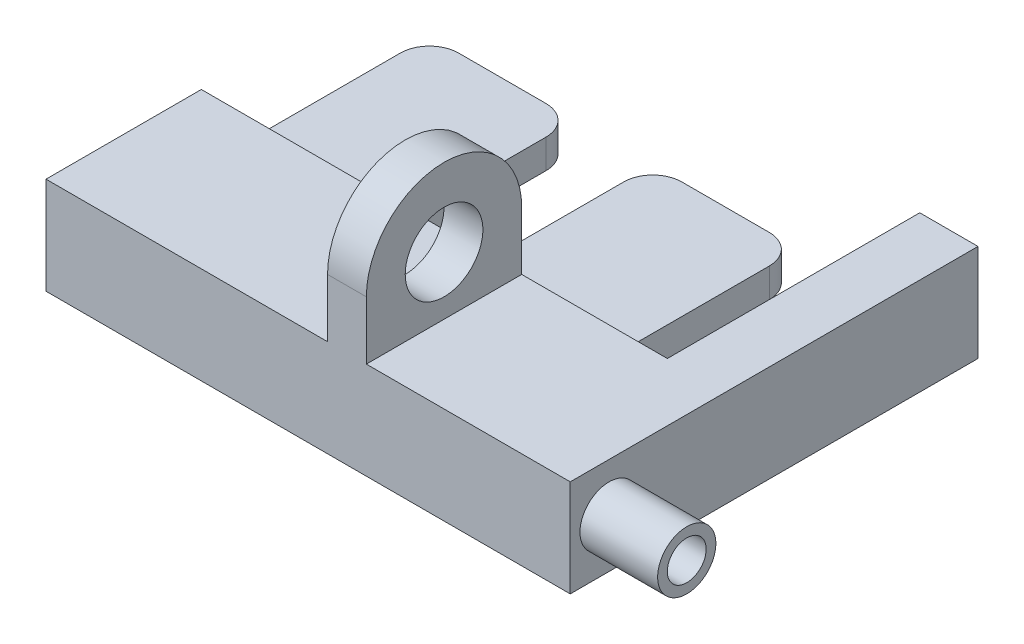
SolidWorks part; units mm, degrees
ref_plane "前视基准面" through (0, 0, 0) normal (0, 0, 1) x (1, 0, 0)
ref_plane "上视基准面" through (0, 0, 0) normal (0, 1, 0) x (1, 0, 0)
ref_plane "右视基准面" through (0, 0, 0) normal (1, 0, 0) x (0, 0, -1)
sketch "草图1" plane through (0, 0, 0) normal (0, 0, 1) x (1, 0, 0)
  line L1 (13.5, -2.5) -> (-13.5, -2.5)
  line L2 (13.5, -2.5) -> (13.5, 2.5)
  line L3 (13.5, 2.5) -> (-13.5, 2.5)
  line L4 (-13.5, -2.5) -> (-13.5, 2.5)
  line L5 (13.5, -2.5) -> (-13.5, 2.5) construction
  line L6 (13.5, 2.5) -> (-13.5, -2.5) construction
  point P0 (0, 0)
  dimension "D1" = 27
  dimension "D2" = 5
extrude "凸台-拉伸1" add sketch "草图1" along normal blind 8
sketch "草图2" plane through (0, 0, 0) normal (0, 0, -1) x (-1, 0, 0)
  line L0 (13.5, -2.5) -> (-13.5, -2.5) construction
  line L1 (-13.5, 2.5) -> (-10.5, 2.5)
  line L2 (-13.5, 2.5) -> (-13.5, -2.5)
  line L3 (-13.5, -2.5) -> (-10.5, -2.5)
  line L4 (-10.5, 2.5) -> (-10.5, -2.5)
  dimension "D1" = 3
extrude "凸台-拉伸2" add sketch "草图2" along normal blind 13
sketch "草图3" plane through (0, 0, -13) normal (0, 0, -1) x (-1, 0, 0)
  line L0 (-13.5, 0) -> (-10.5, 0) construction
  line L1 (-13.5, 2.5) -> (-13.5, -2.5) construction
  line L2 (-10.5, -2.5) -> (-10.5, 2.5) construction
  line L3 (-12, 2.5) -> (-12, -2.5) construction
  line L4 (-10.5, 2.5) -> (-13.5, 2.5) construction
  line L5 (-13.5, -2.5) -> (-10.5, -2.5) construction
  circle A0 centre (-12, 1.3) radius 0.5
  circle A1 centre (-12, -1.3) radius 0.5
  dimension "D1" = 1
  dimension "D2" = 1.3
extrude "切除-拉伸1" cut sketch "草图3" against normal blind 3
sketch "草图4" plane through (13.5, 0, 0) normal (1, 0, 0) x (0, 0, -1)
  line L0 (-6, 2.5) -> (-6, -2.5) construction
  line L1 (-8, 2.5) -> (13, 2.5) construction
  line L2 (-8, -2.5) -> (13, -2.5) construction
  line L3 (-8, 0) -> (13, 0) construction
  line L4 (-8, -2.5) -> (-8, 2.5) construction
  line L5 (13, 2.5) -> (13, -2.5) construction
  circle A0 centre (-6, 0) radius 1.5
  circle A1 centre (-6, 0) radius 1
  dimension "D2" = 3
  dimension "D3" = 2
  dimension "D1" = 2
extrude "凸台-拉伸3" add sketch "草图4" along normal blind 4
ref_plane "基准面1" through (1, 0, 0) normal (-1, 0, 0) x (0, 0, 1)
sketch "草图6" plane through (1, 0, 0) normal (-1, 0, 0) x (0, 0, 1)
  line L0 (8, 2.5) -> (0, 2.5)
  line L1 (0, 2.5) -> (0, 5.5)
  line L2 (8, 2.5) -> (8, 5.5)
  arc A0 (0, 5.5) -> (8, 5.5) centre (4, 5.5) cw
  circle A1 centre (4, 5.5) radius 2
  dimension "D2" = 4
  dimension "D1" = 3
extrude "凸台-拉伸5" add sketch "草图6" against normal blind 2
sketch "草图7" plane through (0, 0, 0) normal (0, 0, -1) x (-1, 0, 0)
  line L0 (13.5, 0) -> (-10.5, 0) construction
  line L1 (13.5, 2.5) -> (13.5, -2.5) construction
  line L2 (-10.5, -2.5) -> (-10.5, 2.5) construction
  line L3 (8, 2.5) -> (8, -2.5) construction
  line L4 (-1, 2.5) -> (13.5, 2.5) construction
  line L5 (13.5, -2.5) -> (-10.5, -2.5) construction
  line L6 (-3.5, 2.5) -> (-3.5, -2.5) construction
  line L7 (-10.5, 2.5) -> (-3, 2.5) construction
  line L9 (0.25, -0.75) -> (-7.25, -0.75)
  line L10 (0.25, -0.75) -> (0.25, 0.75)
  line L11 (0.25, 0.75) -> (-7.25, 0.75)
  line L12 (-7.25, -0.75) -> (-7.25, 0.75)
  line L13 (0.25, -0.75) -> (-7.25, 0.75) construction
  line L14 (0.25, 0.75) -> (-7.25, -0.75) construction
  line L15 (11.75, -0.75) -> (4.25, -0.75)
  line L16 (11.75, -0.75) -> (11.75, 0.75)
  line L17 (11.75, 0.75) -> (4.25, 0.75)
  line L18 (4.25, -0.75) -> (4.25, 0.75)
  line L19 (11.75, -0.75) -> (4.25, 0.75) construction
  line L20 (11.75, 0.75) -> (4.25, -0.75) construction
  point P16 (-3.5, 0)
  point P21 (8, 0)
  dimension "D1" = 5.5
  dimension "D2" = 7
  dimension "D3" = 7.5
  dimension "D4" = 1.5
  dimension "D5" = 7.5
  dimension "D6" = 1.5
extrude "凸台-拉伸6" add sketch "草图7" along normal blind 10
fillet "圆角1" radius 1.5 4 edges at (-11.75, 0, -10) (-4.25, 0, -10) (7.25, 0, -10) (-0.25, 0, -10)
